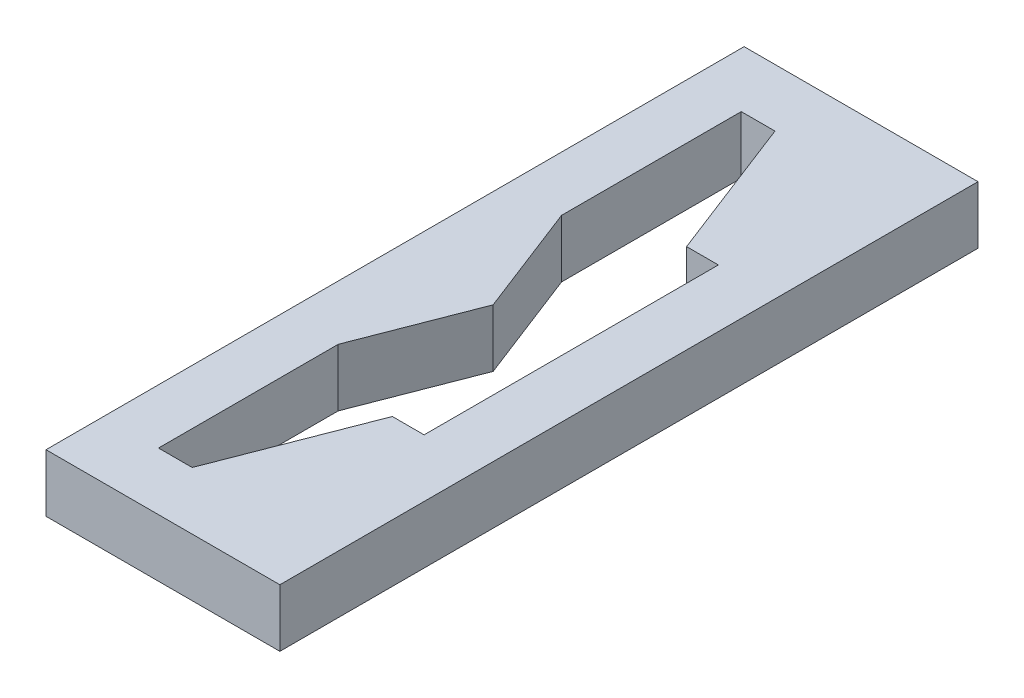
SolidWorks part; units mm, degrees
ref_plane "정면" through (0, 0, 0) normal (0, 0, 1) x (1, 0, 0)
ref_plane "윗면" through (0, 0, 0) normal (0, 1, 0) x (1, 0, 0)
ref_plane "우측면" through (0, 0, 0) normal (1, 0, 0) x (0, 0, -1)
sketch "스케치5" plane through (0, 0, 0) normal (0, 1, 0) x (1, 0, 0)
  line L0 (1, 0) -> (0, 0) construction
  line L1 (0, 0) -> (0, -6.11) construction
  line L2 (0, -6.11) -> (1.5069, -10) construction
  line L3 (1.5069, -10) -> (4.0069, -10) construction
  line L4 (4.0069, -15) -> (4.0069, -5) construction
  line L5 (4.0069, -5) -> (2.9369, -5) construction
  line L6 (2.9369, -5) -> (1, 0) construction
  line L13 (0, -13.89) -> (1.5069, -10) construction
  line L14 (0, -20) -> (0, -13.89) construction
  line L15 (1, -20) -> (0, -20) construction
  line L16 (2.9369, -15) -> (1, -20) construction
  line L17 (4.0069, -15) -> (2.9369, -15) construction
  line L18 (-0.1, -13.8713) -> (1.3997, -10)
  line L19 (-0.1, -6.1287) -> (1.3997, -10)
  line L20 (-0.1, 0.1) -> (-0.1, -6.1287)
  line L21 (1.0685, 0.1) -> (-0.1, 0.1)
  line L22 (3.0054, -4.9) -> (1.0685, 0.1)
  line L23 (4.1069, -4.9) -> (3.0054, -4.9)
  line L24 (4.1069, -15.1) -> (4.1069, -4.9)
  line L25 (4.1069, -15.1) -> (3.0054, -15.1)
  line L26 (3.0054, -15.1) -> (1.0685, -20.1)
  line L27 (1.0685, -20.1) -> (-0.1, -20.1)
  line L28 (-0.1, -20.1) -> (-0.1, -13.8713)
  line L30 (-2, -22.1) -> (6.1069, -22.1)
  line L31 (-2, -22.1) -> (-2, 2.1)
  line L32 (-2, 2.1) -> (6.1069, 2.1)
  line L33 (6.1069, -22.1) -> (6.1069, 2.1)
  line L34 (-2, -22.1) -> (6.1069, 2.1) construction
  line L35 (-2, 2.1) -> (6.1069, -22.1) construction
  point P26 (2.0535, -10)
  dimension "D1" = 1
  dimension "D2" = 5
  dimension "D3" = 1.07
  dimension "D4" = 2.5
  dimension "D5" = 6.11
  dimension "D6" = 5
  dimension "D8" = 2
  dimension "D9" = 2
  dimension "D10" = 2
  dimension "D7" = 0.1
extrude "보스-돌출3" add sketch "스케치5" along normal blind 2 contours L22 L21 L20 L19 L18 L28 L27 L26 L25 L24 L23
